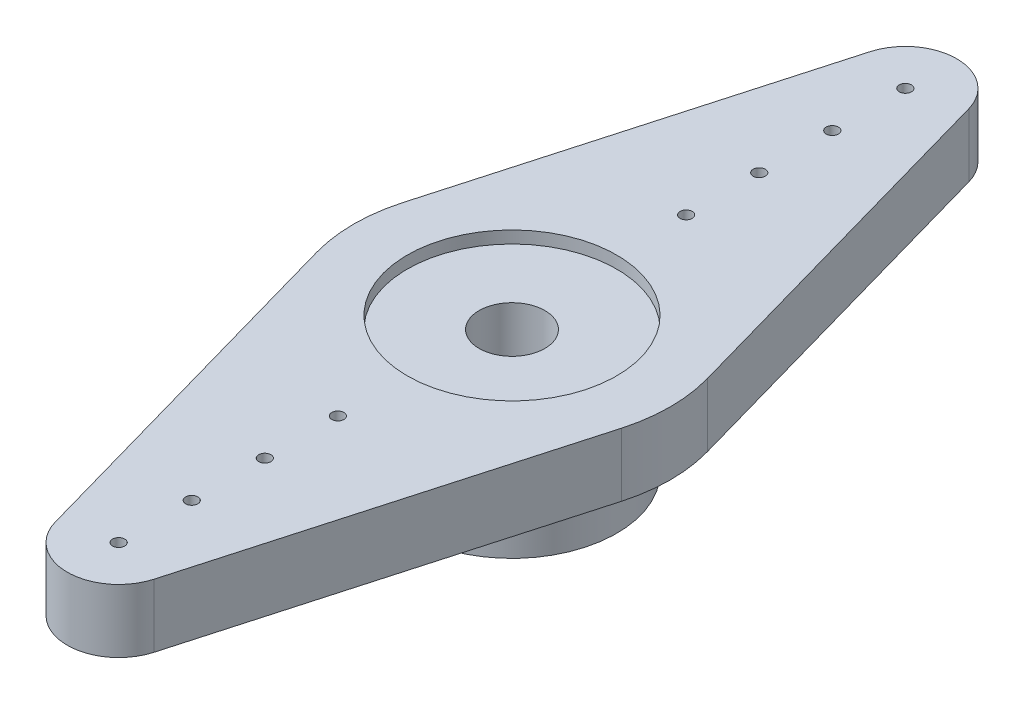
SolidWorks part; units mm, degrees
ref_plane "Front Plane" through (0, 0, 0) normal (0, 0, 1) x (1, 0, 0)
ref_plane "Top Plane" through (0, 0, 0) normal (0, 1, 0) x (1, 0, 0)
ref_plane "Right Plane" through (0, 0, 0) normal (1, 0, 0) x (0, 0, -1)
sketch "Sketch2" plane through (0, 0, 0) normal (0, 1, 0) x (1, 0, 0)
  circle A0 centre (0, 0) radius 2.75
  circle A1 centre (0, 0) radius 4.3
  dimension "D1" = 5.5
  dimension "D2" = 8.6
extrude "Boss-Extrude1" add sketch "Sketch2" along normal blind 3
sketch "Sketch3" plane through (0, 3, 0) normal (0, 1, 0) x (1, 0, 0)
  circle A0 centre (0, 0) radius 4.3
  circle A1 centre (0, 0) radius 1.35
  circle A3 centre (0, 0) radius 4.3 construction
  dimension "D1" = 2.7
extrude "Boss-Extrude2" add sketch "Sketch3" along normal blind 2.1 separate body
sketch "Sketch4" plane through (0, 5.1, 0) normal (0, 1, 0) x (1, 0, 0)
  line L0 (0, 0) -> (0, 16.15) construction
  line L1 (-2.0306, 16.7236) -> (-6.2553, 1.7669)
  line L2 (2.0306, 16.7236) -> (6.2553, 1.7669)
  line L3 (-6.5, 0) -> (6.5, 0) construction
  line L4 (2.0306, -16.7236) -> (6.2553, -1.7669)
  line L5 (-2.0306, -16.7236) -> (-6.2553, -1.7669)
  circle A0 centre (0, 0) radius 4.3
  arc A1 (-6.2553, 1.7669) -> (-6.2553, -1.7669) centre (0, 0) ccw
  circle A2 centre (0, 16.15) radius 0.25
  circle A3 centre (0, 0) radius 4.3 construction
  arc A4 (2.0306, 16.7236) -> (-2.0306, 16.7236) centre (0, 16.15) ccw
  circle A9 centre (0, 13.15) radius 0.25
  circle A10 centre (0, 10.15) radius 0.25
  circle A11 centre (0, 7.15) radius 0.25
  circle A12 centre (0, -7.15) radius 0.25
  circle A13 centre (0, -10.15) radius 0.25
  circle A14 centre (0, -13.15) radius 0.25
  circle A15 centre (0, -16.15) radius 0.25
  arc A16 (2.0306, -16.7236) -> (-2.0306, -16.7236) centre (0, -16.15) cw
  arc A17 (6.2553, -1.7669) -> (6.2553, 1.7669) centre (0, 0) ccw
  dimension "D1" = 13
  dimension "D3" = 4.22
  dimension "D4" = 0.5
  dimension "D6" = 3
  dimension "D2" = 16.15
  dimension "D5" = 4
extrude "Boss-Extrude3" add sketch "Sketch4" against normal blind 2.1 and the other way blind 0.5
